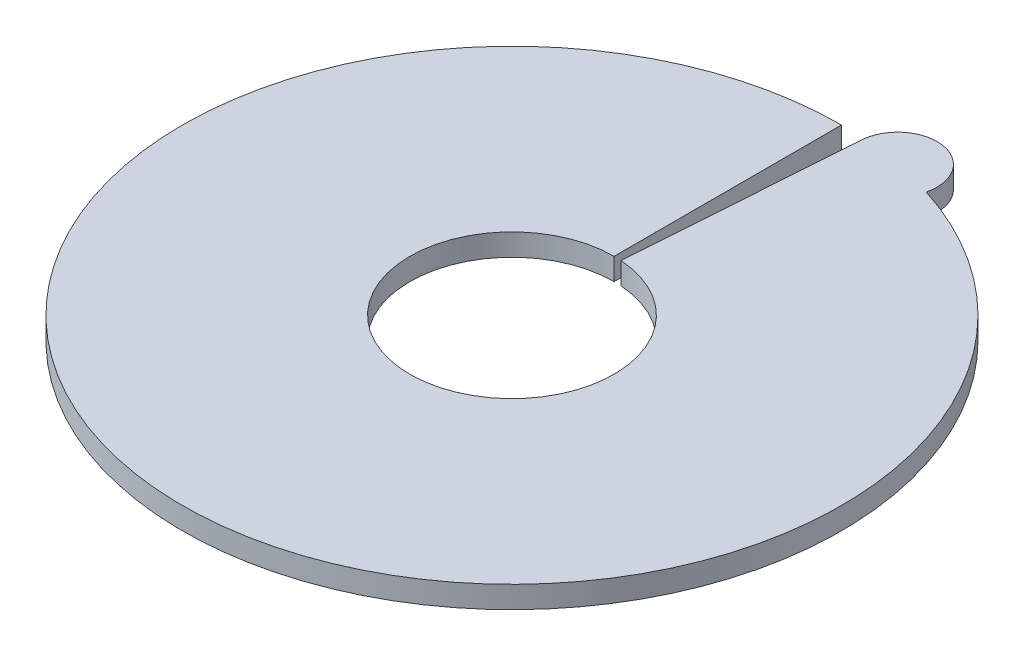
SolidWorks part; units mm, degrees
ref_plane "Front Plane" through (0, 0, 0) normal (0, 0, 1) x (1, 0, 0)
ref_plane "Top Plane" through (0, 0, 0) normal (0, 1, 0) x (1, 0, 0)
ref_plane "Right Plane" through (0, 0, 0) normal (1, 0, 0) x (0, 0, -1)
sketch "Sketch1" plane through (0, 0, 0) normal (0, 1, 0) x (1, 0, 0)
  line L0 (0, 15) -> (0, 4.65)
  line L1 (0.3262, 4.6385) -> (1.0521, 14.9631)
  arc A0 (4.5673, 14.2878) -> (0, 15) centre (0, 0) cw
  arc A2 (1.0521, 14.9631) -> (4.5673, 14.2878) centre (2.8299, 14.7306) cw
  arc A3 (0, 4.65) -> (0.3262, 4.6385) centre (0, 0) ccw
extrude "Boss-Extrude2" add sketch "Sketch1" along normal blind 1 contours A0 L0 A3 L1 A2
